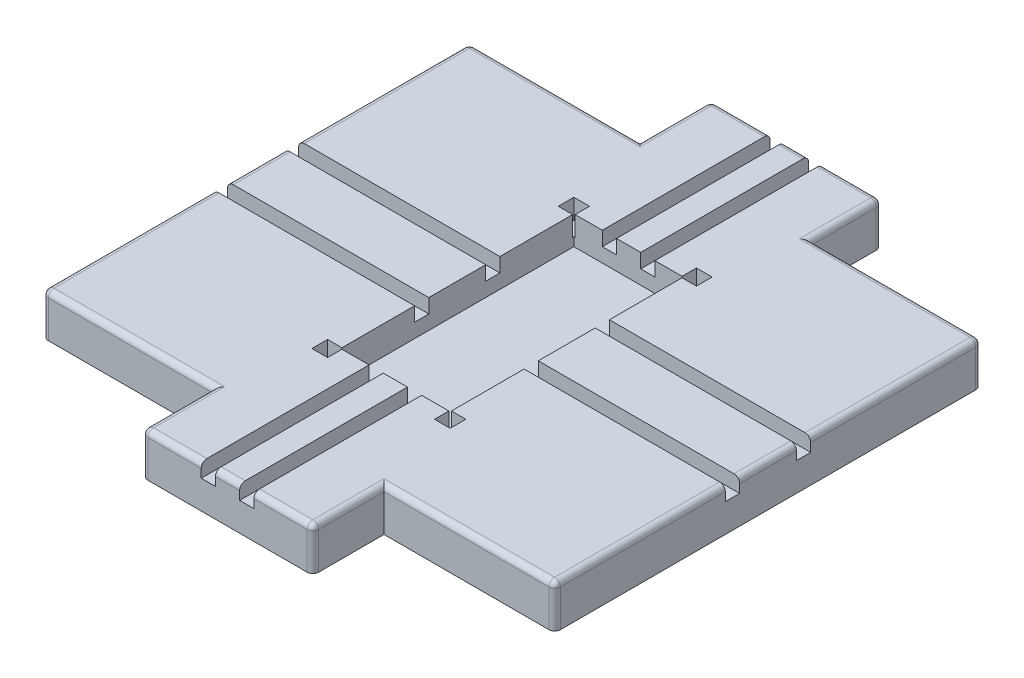
SolidWorks part; units mm, degrees
ref_plane "Front Plane" through (0, 0, 0) normal (0, 0, 1) x (1, 0, 0)
ref_plane "Top Plane" through (0, 0, 0) normal (0, 1, 0) x (1, 0, 0)
ref_plane "Right Plane" through (0, 0, 0) normal (1, 0, 0) x (0, 0, -1)
sketch "Sketch1" plane through (0, 0, 0) normal (0, 1, 0) x (1, 0, 0)
  line L1 (-90, -75) -> (90, -75)
  line L2 (-90, -75) -> (-90, 75)
  line L3 (-90, 75) -> (90, 75)
  line L4 (90, -75) -> (90, 75)
  line L5 (-90, -75) -> (90, 75) construction
  line L6 (-90, 75) -> (90, -75) construction
  point P0 (0, 0)
  dimension "D1" = 180
  dimension "D2" = 150
extrude "Boss-Extrude1" add sketch "Sketch1" along normal blind 15
sketch "Sketch2" plane through (0, 15, 0) normal (0, 1, 0) x (1, 0, 0)
  line L1 (-19.25, -41) -> (19.25, -41)
  line L2 (-19.25, -41) -> (-19.25, 41)
  line L3 (-19.25, 41) -> (19.25, 41)
  line L4 (19.25, -41) -> (19.25, 41)
  line L5 (-19.25, -41) -> (19.25, 41) construction
  line L6 (-19.25, 41) -> (19.25, -41) construction
  point P0 (0, 0)
  dimension "D1" = 82
  dimension "D2" = 38.5
sketch "Sketch7" plane through (0, 0, 0) normal (0, 1, 0) x (1, 0, 0)
  line L0 (0, 75) -> (0, 100) construction
  line L1 (90, 75) -> (-90, 75) construction
  line L2 (-90, -75) -> (90, -75) construction
  line L3 (0, -75) -> (0, -100) construction
  line L5 (-30, 75) -> (30, 75)
  line L6 (-30, 75) -> (-30, 100)
  line L7 (-30, 100) -> (30, 100)
  line L8 (30, 75) -> (30, 100)
  line L9 (-30, 75) -> (30, 100) construction
  line L10 (-30, 100) -> (30, 75) construction
  line L11 (-30, -100) -> (30, -100)
  line L12 (-30, -100) -> (-30, -75)
  line L13 (-30, -75) -> (30, -75)
  line L14 (30, -100) -> (30, -75)
  line L15 (-30, -100) -> (30, -75) construction
  line L16 (-30, -75) -> (30, -100) construction
  point P7 (0, 87.5)
  point P15 (0, -87.5)
  dimension "D1" = 25
  dimension "D2" = 25
  dimension "D3" = 60
  dimension "D4" = 60
extrude "Boss-Extrude6" add sketch "Sketch7" along normal blind 15 contours L11 L14 L13 L12 | L5 L8 L7 L6
fillet "Fillet1" radius 2 20 edges at (90, 7.5, -75) (90, 7.5, 75) (30, 7.5, -100) (30, 15, -87.5) (60, 15, -75) (0, 15, -100) (-30, 15, -87.5) (-60, 15, -75) (-60, 15, 75) (-30, 15, 87.5) (30, 15, 87.5) (60, 15, 75) (90, 15, 0) (-90, 15, 0) (0, 15, 100) (30, 7.5, 100) (-30, 7.5, 100) (-90, 7.5, 75) (-90, 7.5, -75) (-30, 7.5, -100)
sketch "Sketch10" plane through (0, 15, 0) normal (0, 1, 0) x (1, 0, 0)
  line L0 (-9.25, -40.5) -> (-9.25, -33.1629)
  line L15 (-99.0229, 15) -> (-19.25, 15)
  line L22 (-99.0229, 10) -> (-19.25, 10)
  line L24 (-9.25, -105.688) -> (-4.25, -105.688)
  line L27 (-4.25, -105.688) -> (-4.25, -40.5)
  line L32 (-99.0229, 15) -> (-99.0229, 10)
  line L33 (-9.25, -40.5) -> (-9.25, -105.688)
  line L34 (-9.25, -33.1629) -> (-4.25, -33.1629)
  line L35 (-4.25, -33.1629) -> (-4.25, -40.5)
  line L36 (-19.25, 10) -> (-11.5551, 10)
  line L37 (-11.5551, 10) -> (-11.5551, 15)
  line L38 (-11.5551, 15) -> (-19.25, 15)
  dimension "D3" = 5
  dimension "D6" = 5
extrude "Cut-Extrude1" cut sketch "Sketch2" along direction (0, -1, 0) on the side against the normal blind 10
extrude "Cut-Extrude3" cut sketch "Sketch10" against normal blind 5
sketch "Sketch11" plane through (0, 15, 0) normal (0, 1, 0) x (1, 0, 0)
  line L6 (-19.25, 41) -> (-24.2997, 46.0497) construction
  line L8 (-24.2997, 46.0497) -> (-18.7997, 46.0497)
  line L9 (-24.2997, 46.0497) -> (-24.2997, 40.5497)
  line L10 (-24.2997, 40.5497) -> (-18.7997, 40.5497)
  line L11 (-18.7997, 46.0497) -> (-18.7997, 40.5497)
  dimension "D1" = 7.1414
  dimension "D2" = 5.5
  dimension "D3" = 5.5
extrude "Cut-Extrude6" cut sketch "Sketch11" against normal blind 7
mirror "Mirror3" about plane through (0, 0, 0) normal (1, 0, 0) of "Cut-Extrude6" second plane through (0, 0, 0) second plane normal (0, 0, 1)
mirror "Mirror4" about plane through (0, 0, 0) normal (1, 0, 0) of "Cut-Extrude3" second plane through (0, 0, 0) second plane normal (0, 0, 1)
